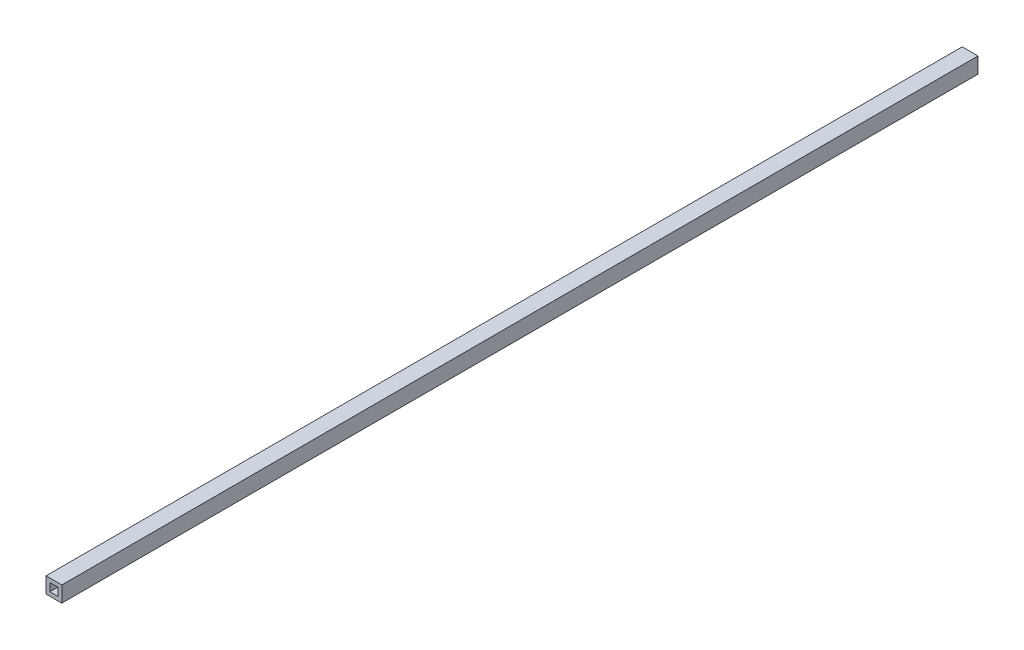
SolidWorks part; units mm, degrees
material "6063-O"
ref_plane "Front Plane" through (0, 0, 0) normal (0, 0, 1) x (1, 0, 0)
ref_plane "Top Plane" through (0, 0, 0) normal (0, 1, 0) x (1, 0, 0)
ref_plane "Right Plane" through (0, 0, 0) normal (1, 0, 0) x (0, 0, -1)
sketch "Sketch1" plane through (0, 0, 0) normal (0, 0, 1) x (1, 0, 0)
  line L1 (-10, -10) -> (10, -10)
  line L2 (-10, -10) -> (-10, 10)
  line L3 (-10, 10) -> (10, 10)
  line L4 (10, -10) -> (10, 10)
  line L5 (-10, -10) -> (10, 10) construction
  line L6 (-10, 10) -> (10, -10) construction
  point P0 (0, 0)
  dimension "D1" = 20
extrude "Extrude-Thin1" add sketch "Sketch1" along normal blind 1160 thin thin type one direction reverse wall 5
